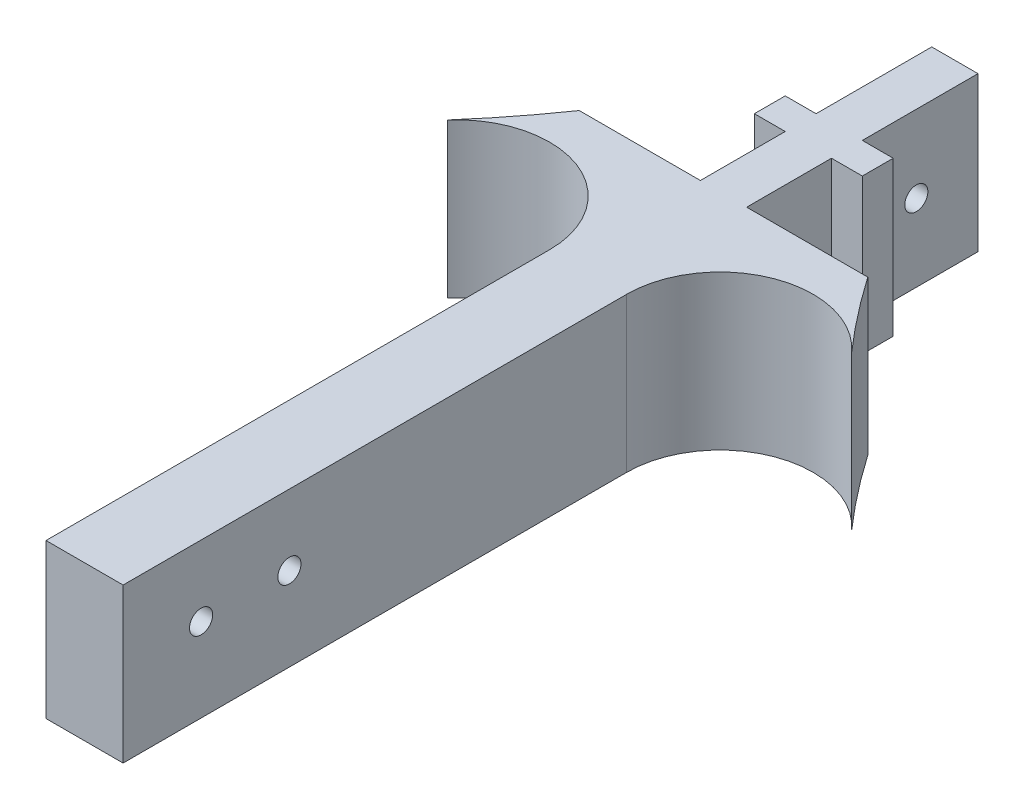
SolidWorks part; units mm, degrees
ref_plane "Plan de face" through (0, 0, 0) normal (0, 0, 1) x (1, 0, 0)
ref_plane "Plan de dessus" through (0, 0, 0) normal (0, 1, 0) x (1, 0, 0)
ref_plane "Plan de droite" through (0, 0, 0) normal (1, 0, 0) x (0, 0, -1)
sketch "Esquisse1" plane through (0, 0, 0) normal (0, 1, 0) x (1, 0, 0)
  line L0 (-3, 84.3983) -> (-3, 69.3983)
  line L1 (-3, 84.3983) -> (0, 84.3983)
  line L2 (-3, 65.3983) -> (-3, 54.3983)
  line L3 (-5, -28.4678) -> (0, -28.4678)
  line L4 (0, 84.3983) -> (0, -28.4678)
  line L5 (-3, 69.3983) -> (-7, 69.3983)
  line L6 (-3, 54.3983) -> (-18.71, 54.3983)
  line L7 (-3, 65.3983) -> (-7, 65.3983)
  line L8 (-7, 69.3983) -> (-7, 65.3983)
  line L9 (-5, 36.8425) -> (-5, -28.4678)
  line L10 (8.1242, -28.4678) -> (-5.9587, -28.4678) construction
  arc A0 (-26.1833, 44.8157) -> (-18.71, 54.3983) centre (-105.5, 114.3795) ccw
  arc A1 (-5, 36.8425) -> (-26.1833, 44.8157) centre (-17.0922, 36.8425) ccw
  dimension "D7" = 211
  dimension "D1" = 3
  dimension "D2" = 4
  dimension "D3" = 4
  dimension "D4" = 15
  dimension "D5" = 11
  dimension "D6" = 15.71
extrude "Boss.-Extru.1" add sketch "Esquisse1" along normal blind 20
mirror "Symétrie1" about plane through (0, 20, -84.3983) normal (-1, 0, 0) of "Boss.-Extru.1"
sketch "Esquisse3" plane through (-3, 0, 0) normal (-1, 0, 0) x (0, 0, 1)
  line L2 (-84.3983, 20) -> (-69.3983, 20) construction
  line L3 (-65.3983, 20) -> (-54.3983, 20) construction
  line L4 (-84.3983, 20) -> (-84.3983, 0) construction
  circle A0 centre (-76.3983, 10) radius 1.5
  circle A1 centre (-60.3983, 10) radius 1.5
  dimension "D1" = 3
  dimension "D2" = 3
  dimension "D3" = 10
  dimension "D4" = 10
  dimension "D5" = 8
  dimension "D6" = 24
extrude "Enlèv. mat.-Extru.3" cut sketch "Esquisse3" against normal blind 20
sketch "Esquisse4" plane through (5, 0, 0) normal (1, 0, 0) x (0, 0, -1)
  circle A0 centre (-18.3543, 10.8445) radius 1.5
extrude "Enlèv. mat.-Extru.4" cut sketch "Esquisse4" against normal blind 10
sketch "Esquisse5" plane through (5, 0, 0) normal (1, 0, 0) x (0, 0, -1)
  circle A0 centre (-6.9025, 10.8445) radius 1.5
extrude "Enlèv. mat.-Extru.5" cut sketch "Esquisse5" against normal blind 10
